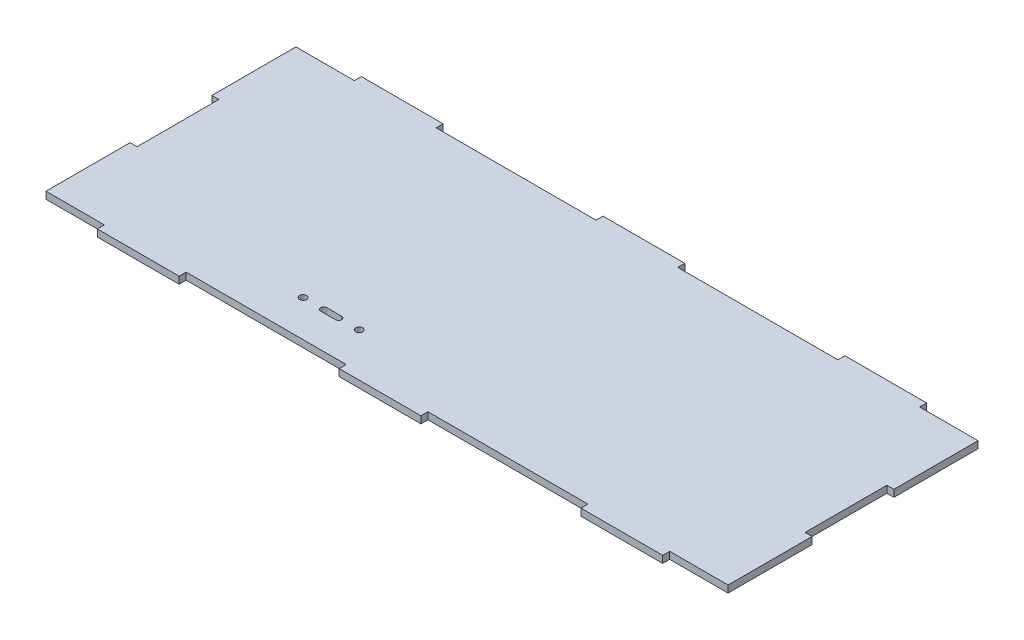
SolidWorks part; units mm, degrees
ref_plane "Front Plane" through (0, 0, 0) normal (0, 0, 1) x (1, 0, 0)
ref_plane "Top Plane" through (0, 0, 0) normal (0, 1, 0) x (1, 0, 0)
ref_plane "Right Plane" through (0, 0, 0) normal (1, 0, 0) x (0, 0, -1)
sketch "Sketch1" plane through (0, 0, 0) normal (0, 1, 0) x (1, 0, 0)
  line L1 (-146, 53.5) -> (146, 53.5)
  line L2 (-146, 53.5) -> (-146, -53.5)
  line L3 (-146, -53.5) -> (146, -53.5)
  line L4 (146, 53.5) -> (146, -53.5)
  line L5 (-146, 53.5) -> (146, -53.5) construction
  line L6 (-146, -53.5) -> (146, 53.5) construction
  point P0 (0, 0)
  point P6 (-210.2596, -52.4466)
  dimension "D1" = 292
  dimension "D2" = 107
extrude "Boss-Extrude1" add sketch "Sketch1" along normal blind 3
sketch "Sketch4" plane through (0, 3, 0) normal (0, 1, 0) x (1, 0, 0)
  line L0 (-146, 53.5) -> (-146, -53.5) construction
  line L1 (-121, -53.5) -> (-86, -53.5)
  line L2 (-121, -53.5) -> (-121, -56.5)
  line L3 (-121, -56.5) -> (-86, -56.5)
  line L4 (-86, -53.5) -> (-86, -56.5)
  line L5 (-121, -53.5) -> (-86, -56.5) construction
  line L6 (-121, -56.5) -> (-86, -53.5) construction
  line L8 (-1.65, 0) -> (1.65, 0) construction
  line L9 (-86, 53.5) -> (-86, 56.5)
  line L10 (-121, 53.5) -> (-86, 53.5)
  line L11 (-121, 56.5) -> (-86, 56.5)
  line L12 (-121, 53.5) -> (-121, 56.5)
  line L13 (0, -1.65) -> (0, 1.65) construction
  line L14 (86, 53.5) -> (86, 56.5)
  line L15 (121, 53.5) -> (121, 56.5)
  line L16 (121, 56.5) -> (86, 56.5)
  line L17 (121, 53.5) -> (86, 53.5)
  line L18 (86, -53.5) -> (86, -56.5)
  line L19 (121, -53.5) -> (121, -56.5)
  line L20 (121, -53.5) -> (86, -53.5)
  line L21 (121, -56.5) -> (86, -56.5)
  line L22 (-146, -53.5) -> (146, -53.5) construction
  point P0 (-103.5, -55)
  dimension "D1" = 3
  dimension "D2" = 35
  dimension "D3" = 25
  dimension "D4" = 0
sketch "Sketch7" plane through (0, 3, 0) normal (0, 1, 0) x (1, 0, 0)
  line L1 (-17.5, -53.5) -> (17.5, -53.5)
  line L2 (-17.5, -53.5) -> (-17.5, -56.5)
  line L3 (-17.5, -56.5) -> (17.5, -56.5)
  line L4 (17.5, -53.5) -> (17.5, -56.5)
  line L5 (-17.5, -53.5) -> (17.5, -56.5) construction
  line L6 (-17.5, -56.5) -> (17.5, -53.5) construction
  line L7 (0, -1.65) -> (0, 1.65) construction
  line L8 (-1.65, 0) -> (1.65, 0) construction
  line L9 (-17.5, 56.5) -> (17.5, 56.5)
  line L10 (17.5, 53.5) -> (17.5, 56.5)
  line L11 (-17.5, 53.5) -> (17.5, 53.5)
  line L12 (-17.5, 53.5) -> (-17.5, 56.5)
  line L13 (-146, -53.5) -> (146, -53.5) construction
  point P0 (0, -55)
  dimension "D1" = 35
  dimension "D2" = 0
  dimension "D3" = 0
  dimension "D4" = 3
sketch "Sketch8" plane through (0, 3, 0) normal (0, 1, 0) x (1, 0, 0)
  line L0 (-1.65, 0) -> (1.65, 0) construction
  line L1 (146, 17.5) -> (143, 17.5)
  line L2 (146, 17.5) -> (146, -17.5)
  line L3 (146, -17.5) -> (143, -17.5)
  line L4 (143, 17.5) -> (143, -17.5)
  line L5 (146, 17.5) -> (143, -17.5) construction
  line L6 (146, -17.5) -> (143, 17.5) construction
  line L7 (146, -53.5) -> (146, 53.5) construction
  line L8 (0, -1.65) -> (0, 1.65) construction
  line L9 (-146, -17.5) -> (-143, -17.5)
  line L10 (-143, 17.5) -> (-143, -17.5)
  line L11 (-146, 17.5) -> (-143, 17.5)
  line L12 (-146, 17.5) -> (-146, -17.5)
  point P0 (144.5, 0)
  dimension "D1" = 35
  dimension "D2" = 3
  dimension "D3" = 0
  dimension "D4" = 0
extrude "Cut-Extrude7" cut sketch "Sketch8" against normal blind 3
extrude "Boss-Extrude2" add sketch "Sketch7" against normal blind 3
extrude "Boss-Extrude3" add sketch "Sketch4" against normal blind 3
sketch "Sketch9" plane through (0, 3, 0) normal (0, 1, 0) x (1, 0, 0)
  line L0 (-42.7658, -37.8606) -> (-36.3658, -37.8606) construction
  line L1 (-42.7658, -36.5606) -> (-36.3658, -36.5606)
  line L2 (-42.7658, -39.1606) -> (-36.3658, -39.1606)
  line L3 (-86, -53.5) -> (-17.5, -53.5) construction
  line L4 (-39.5658, -37.8606) -> (-39.5658, -36.7086) construction
  arc A0 (-42.7658, -36.5606) -> (-42.7658, -39.1606) centre (-42.7658, -37.8606) ccw
  arc A1 (-36.3658, -39.1606) -> (-36.3658, -36.5606) centre (-36.3658, -37.8606) ccw
  circle A2 centre (-27.5658, -37.8606) radius 1.5
  circle A3 centre (-51.5658, -37.8606) radius 1.5
  point P2 (-39.5658, -37.8606)
  point P7 (-44.0658, -37.8606)
  point P8 (-35.0658, -37.8606)
  dimension "D2" = 2.6
  dimension "D4" = 3
  dimension "D7" = 0
  dimension "D1" = 9
  dimension "D3" = 9
  dimension "D5" = 7.5
  dimension "D6" = 14.3394
extrude "Cut-Extrude8" cut sketch "Sketch9" against normal blind 10
